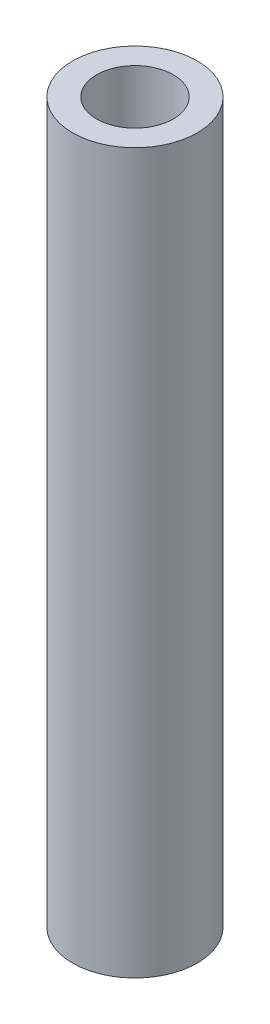
SolidWorks part; units mm, degrees
ref_plane "Front Plane" through (0, 0, 0) normal (0, 0, 1) x (1, 0, 0)
ref_plane "Top Plane" through (0, 0, 0) normal (0, 1, 0) x (1, 0, 0)
ref_plane "Right Plane" through (0, 0, 0) normal (1, 0, 0) x (0, 0, -1)
sketch "Sketch1" plane through (0, 3, 0) normal (0, 1, 0) x (1, 0, 0)
  circle A0 centre (-20, 25) radius 1.6
  circle A1 centre (-20, 25) radius 2.6
extrude "Boss-Extrude1" add sketch "Sketch1" along normal blind 30
